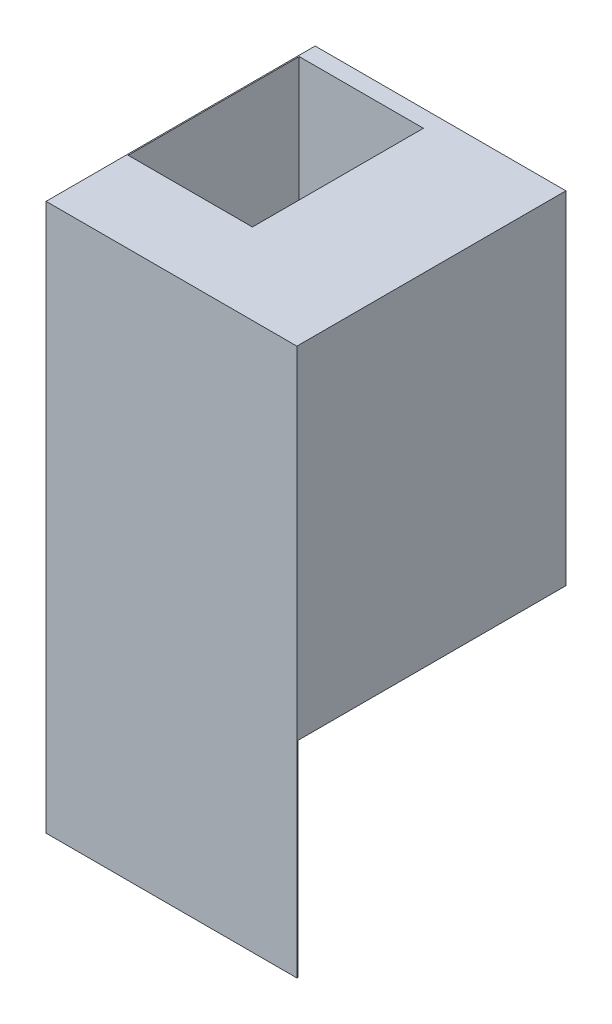
SolidWorks part; units mm, degrees
ref_plane "Plan de face" through (0, 0, 0) normal (0, 0, 1) x (1, 0, 0)
ref_plane "Plan de dessus" through (0, 0, 0) normal (0, 1, 0) x (1, 0, 0)
ref_plane "Plan de droite" through (0, 0, 0) normal (1, 0, 0) x (0, 0, -1)
sketch "Esquisse1" plane through (0, 0, 0) normal (0, 0, 1) x (1, 0, 0)
  line L1 (-19.7567, -134.4601) -> (2180.2433, -134.4601)
  line L2 (-19.7567, -134.4601) -> (-19.7567, 4665.5399)
  line L3 (-19.7567, 4665.5399) -> (2180.2433, 4665.5399)
  line L4 (2180.2433, -134.4601) -> (2180.2433, 4665.5399)
  dimension "D1" = 4800
  dimension "D2" = 2200
extrude "Boss.-Extru.1" add sketch "Esquisse1" along normal blind 10
sketch "Esquisse3" plane through (-19.7567, 0, 0) normal (-1, 0, 0) x (0, 0, 1)
  line L0 (0, 4665.5399) -> (-700, 4665.5399)
  line L1 (0, 4665.5399) -> (0, 3665.5399)
  line L2 (0, 4665.5399) -> (0, -134.4601) construction
  line L3 (0, 3665.5399) -> (-700, 4665.5399)
extrude "Boss.-Extru.3" add sketch "Esquisse3" against normal blind 1100 contours L3 L0 L1
sketch "Esquisse11" plane through (0, 0, 0) normal (0, 0, -1) x (-1, 0, 0)
  line L0 (-1080.2433, 4665.5399) -> (-1080.2433, -134.4601) construction
  line L1 (19.7567, -134.4601) -> (-2180.2433, -134.4601) construction
  line L2 (-2180.2433, 2265.5399) -> (19.7567, 2265.5399) construction
  line L3 (-2180.2433, -134.4601) -> (-2180.2433, 4665.5399) construction
  line L4 (19.7567, 3665.5399) -> (19.7567, -134.4601) construction
  line L6 (-2180.2433, 4665.5399) -> (-1080.2433, 4665.5399)
  line L7 (-2180.2433, 4665.5399) -> (-2180.2433, 1665.5399)
  line L8 (-2180.2433, 1665.5399) -> (-1080.2433, 1665.5399)
  line L9 (-1080.2433, 4665.5399) -> (-1080.2433, 1665.5399)
  dimension "D1" = 3000
extrude "Boss.-Extru.5" add sketch "Esquisse11" along normal blind 2200
sketch "Esquisse12" plane through (0, 0, -2200) normal (0, 0, -1) x (-1, 0, 0)
  line L0 (-1080.2433, 1665.5399) -> (-1080.2433, 4665.5399) construction
  line L1 (-2170.2433, 1675.5399) -> (-1090.2433, 1675.5399)
  line L2 (-2170.2433, 1675.5399) -> (-2170.2433, 4655.5399)
  line L3 (-2170.2433, 4655.5399) -> (-1090.2433, 4655.5399)
  line L4 (-1090.2433, 1675.5399) -> (-1090.2433, 4655.5399)
  line L5 (-2180.2433, 4665.5399) -> (-2180.2433, 1665.5399) construction
  line L6 (-2180.2433, 1665.5399) -> (-1080.2433, 1665.5399) construction
  line L7 (-1080.2433, 4665.5399) -> (-2180.2433, 4665.5399) construction
  dimension "D1" = 10
  dimension "D2" = 10
  dimension "D3" = 10
  dimension "D4" = 10
extrude "Enlèv. mat.-Extru.1" cut sketch "Esquisse12" against normal blind 2200
sketch "Esquisse13" plane through (1080.2433, 0, 0) normal (-1, 0, 0) x (0, 0, 1)
  line L0 (0, 1665.5399) -> (0, 3665.5399) construction
  line L1 (0, 2215.5399) -> (-1450, 2215.5399)
  line L2 (0, 2215.5399) -> (0, 3115.5399)
  line L3 (0, 3115.5399) -> (-1450, 3115.5399)
  line L4 (-1800, 2565.5399) -> (-1800, 2765.5399)
  line L5 (-2200, 1665.5399) -> (0, 1665.5399) construction
  arc A0 (-1450, 3115.5399) -> (-1800, 2765.5399) centre (-1450, 2765.5399) ccw
  arc A1 (-1450, 2215.5399) -> (-1800, 2565.5399) centre (-1450, 2565.5399) cw
  point P10 (-1800, 3115.5399)
  point P13 (-1800, 2215.5399)
  dimension "D4" = 350
  dimension "D1" = 550
  dimension "D2" = 900
  dimension "D3" = 1800
extrude "Enlèv. mat.-Extru.2" cut sketch "Esquisse13" against normal up to next
sketch "Esquisse14" plane through (0, 1665.5399, 0) normal (0, -1, 0) x (1, 0, 0)
  line L1 (2180.2433, -2200) -> (-19.7567, -2200)
  line L2 (2180.2433, -2200) -> (2180.2433, -2350)
  line L3 (2180.2433, -2350) -> (-19.7567, -2350)
  line L4 (-19.7567, -2200) -> (-19.7567, -2350)
  point P5 (2180.2433, -2200)
  dimension "D1" = 2200
  dimension "D2" = 150
extrude "Boss.-Extru.12" add sketch "Esquisse14" against normal up to surface (3000 mm away) up to face at (1080.2433, 4665.5399, -963.3333)
sketch "Esquisse16" plane through (-19.7567, 0, 0) normal (-1, 0, 0) x (0, 0, 1)
  line L0 (0, -134.4601) -> (-1538.868, -134.4601)
  line L1 (0, -134.4601) -> (0, 3665.5399)
  line L2 (0, 3665.5399) -> (-700, 4665.5399)
  line L3 (-700, 4665.5399) -> (-2350, 4665.5399)
  line L4 (-2350, 4665.5399) -> (-2350, -134.4601)
  line L5 (-2350, -134.4601) -> (-1538.868, -134.4601)
extrude "Boss.-Extru.13" add sketch "Esquisse16" against normal blind 10
